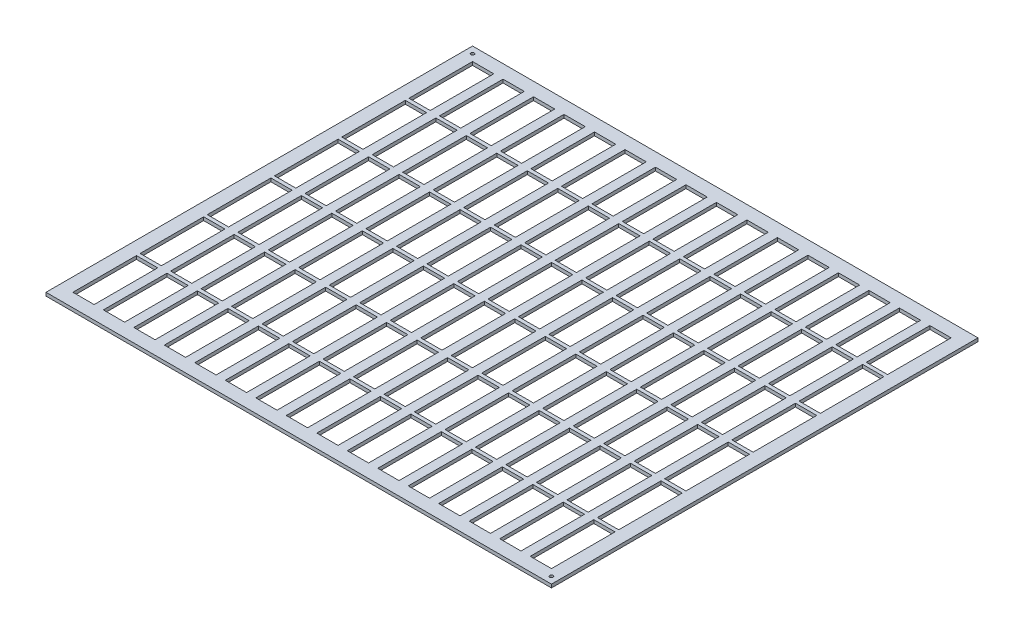
SolidWorks part; units mm, degrees
ref_plane "Front" through (0, 0, 0) normal (0, 0, 1) x (1, 0, 0)
ref_plane "Top" through (0, 0, 0) normal (0, 1, 0) x (1, 0, 0)
ref_plane "Right" through (0, 0, 0) normal (1, 0, 0) x (0, 0, -1)
sketch "Sketch1" plane through (0, 0, 0) normal (0, 1, 0) x (1, 0, 0)
  line L0 (0, -76.0537) -> (0, -227.7466) construction
  line L5 (-238.9187, -201.6125) -> (238.9188, -201.6125)
  line L6 (-238.9187, -201.6125) -> (-238.9187, 201.6125)
  line L7 (-238.9187, 201.6125) -> (238.9188, 201.6125)
  line L8 (238.9188, -201.6125) -> (238.9188, 201.6125)
  line L9 (-238.9187, -201.6125) -> (238.9188, 201.6125) construction
  line L10 (-238.9187, 201.6125) -> (238.9188, -201.6125) construction
  line L11 (55.3206, 0) -> (102.8784, 0) construction
  point P0 (0, 0)
  dimension "D1" = 477.8375
  dimension "D2" = 403.225
extrude "Boss-Extrude1" add sketch "Sketch1" along normal blind 3.175
sketch "Sketch2" plane through (0, 0, 0) normal (0, 1, 0) x (1, 0, 0)
  line L1 (-226.2187, 188.9125) -> (-206.1187, 188.9125)
  line L2 (-226.2187, 188.9125) -> (-226.2187, 128.8125)
  line L3 (-226.2187, 128.8125) -> (-206.1187, 128.8125)
  line L4 (-206.1187, 188.9125) -> (-206.1187, 128.8125)
  line L8 (206.1188, -128.8125) -> (226.2188, -128.8125) construction
  line L9 (206.1188, -128.8125) -> (206.1188, -188.9125) construction
  line L10 (206.1188, -188.9125) -> (226.2188, -188.9125) construction
  line L11 (226.2188, -128.8125) -> (226.2188, -188.9125) construction
  line L12 (-226.2187, -188.9125) -> (226.2188, -188.9125)
  line L13 (226.2188, -188.9125) -> (226.2188, 188.9125)
  line L14 (226.2188, 188.9125) -> (-226.2187, 188.9125)
  line L15 (-226.2187, 188.9125) -> (-226.2187, -188.9125)
  line L16 (-226.2187, -188.9125) -> (226.2188, -188.9125) construction
  line L17 (226.2188, -188.9125) -> (226.2188, 188.9125) construction
  line L18 (226.2188, 188.9125) -> (-226.2187, 188.9125) construction
  line L19 (-226.2187, 188.9125) -> (-226.2187, -188.9125) construction
  line L20 (216.1688, -128.8125) -> (216.1688, -188.9125) construction
  line L21 (206.1188, -158.8625) -> (226.2188, -158.8625) construction
  dimension "D1" = 60.1
  dimension "D2" = 20.1
  dimension "D3" = 12.7
extrude "Cut-Extrude1" cut sketch "Sketch2" along normal through all
pattern_linear "LPattern2" count 16 spacing 28.8225 along (1, 0, 0) count 6 spacing 63.545 along (0, 0, 1) of "Cut-Extrude1"
sketch "Sketch4" plane through (0, 0, 0) normal (0, 1, 0) x (1, 0, 0)
  line L0 (-238.9187, -201.6125) -> (238.9188, -201.6125) construction
  line L1 (238.9188, -201.6125) -> (238.9188, 201.6125) construction
  line L2 (238.9188, 201.6125) -> (-238.9187, 201.6125) construction
  line L3 (-238.9187, 201.6125) -> (-238.9187, -201.6125) construction
  circle A0 centre (-232.5687, 195.2625) radius 1.5875
  circle A1 centre (232.5688, -195.2625) radius 1.5875
  dimension "D3" = 3.175
  dimension "D6" = 3.175
  dimension "D1" = 6.35
  dimension "D2" = 6.35
  dimension "D4" = 6.35
  dimension "D5" = 6.35
extrude "Cut-Extrude2" cut sketch "Sketch4" along normal through all
sketch "v1" plane through (0, 0, 0) normal (0, 1, 0) x (1, 0, 0)
  line L0 (238.9188, -201.6125) -> (238.9188, 201.6125) construction
  line L9 (-238.9187, -201.6125) -> (238.9188, -201.6125) construction
  line L10 (-238.9187, 201.6125) -> (-238.9187, -201.6125) construction
  line L11 (238.9188, 201.6125) -> (-238.9187, 201.6125) construction
  line L12 (238.9188, -201.6125) -> (238.9188, 201.6125)
  line L13 (-238.9187, -201.6125) -> (238.9188, -201.6125)
  line L14 (-238.9187, 201.6125) -> (-238.9187, -201.6125)
  line L15 (238.9188, 201.6125) -> (-238.9187, 201.6125)
  line L16 (-206.1187, 128.8125) -> (-206.1187, 188.9125) construction
  line L17 (-206.1187, 188.9125) -> (-226.2187, 188.9125) construction
  line L18 (-226.2187, 128.8125) -> (-206.1187, 128.8125) construction
  line L19 (-226.2187, 188.9125) -> (-226.2187, 128.8125) construction
  line L20 (-226.2187, 128.8125) -> (-206.1187, 128.8125)
  line L21 (-206.1187, 188.9125) -> (-226.2187, 188.9125)
  line L22 (-206.1187, 128.8125) -> (-206.1187, 188.9125)
  line L23 (-226.2187, 188.9125) -> (-226.2187, 128.8125)
  line L24 (-180.7187, 188.9125) -> (-200.8187, 188.9125)
  line L25 (-226.2187, 188.9125) -> (-206.1187, 188.9125)
  line L26 (-226.2187, 188.9125) -> (-226.2187, 128.8125)
  line L27 (-226.2187, 128.8125) -> (-206.1187, 128.8125)
  line L28 (-206.1187, 188.9125) -> (-206.1187, 128.8125)
  line L29 (-200.8187, 188.9125) -> (-200.8187, 128.8125)
  line L30 (-200.8187, 128.8125) -> (-180.7187, 128.8125)
  line L31 (-180.7187, 128.8125) -> (-180.7187, 188.9125)
  line L32 (-155.3187, 188.9125) -> (-175.4187, 188.9125)
  line L33 (-175.4187, 188.9125) -> (-175.4187, 128.8125)
  line L34 (-175.4187, 128.8125) -> (-155.3187, 128.8125)
  line L35 (-155.3187, 128.8125) -> (-155.3187, 188.9125)
  line L36 (-129.9187, 188.9125) -> (-150.0187, 188.9125)
  line L37 (-150.0187, 188.9125) -> (-150.0187, 128.8125)
  line L38 (-150.0187, 128.8125) -> (-129.9187, 128.8125)
  line L39 (-129.9187, 128.8125) -> (-129.9187, 188.9125)
  line L40 (-104.5187, 188.9125) -> (-124.6187, 188.9125)
  line L41 (-124.6187, 188.9125) -> (-124.6187, 128.8125)
  line L42 (-124.6187, 128.8125) -> (-104.5187, 128.8125)
  line L43 (-104.5187, 128.8125) -> (-104.5187, 188.9125)
  line L44 (-79.1187, 188.9125) -> (-99.2187, 188.9125)
  line L45 (-99.2187, 188.9125) -> (-99.2187, 128.8125)
  line L46 (-99.2187, 128.8125) -> (-79.1187, 128.8125)
  line L47 (-79.1187, 128.8125) -> (-79.1187, 188.9125)
  line L48 (-53.7187, 188.9125) -> (-73.8187, 188.9125)
  line L49 (-73.8187, 188.9125) -> (-73.8187, 128.8125)
  line L50 (-73.8187, 128.8125) -> (-53.7187, 128.8125)
  line L51 (-53.7187, 128.8125) -> (-53.7187, 188.9125)
  line L52 (-28.3187, 188.9125) -> (-48.4187, 188.9125)
  line L53 (-48.4187, 188.9125) -> (-48.4187, 128.8125)
  line L54 (-48.4187, 128.8125) -> (-28.3187, 128.8125)
  line L55 (-28.3187, 128.8125) -> (-28.3187, 188.9125)
  line L56 (-2.9187, 188.9125) -> (-23.0187, 188.9125)
  line L57 (-23.0187, 188.9125) -> (-23.0187, 128.8125)
  line L58 (-23.0187, 128.8125) -> (-2.9187, 128.8125)
  line L59 (-2.9187, 128.8125) -> (-2.9187, 188.9125)
  line L60 (22.4813, 188.9125) -> (2.3813, 188.9125)
  line L61 (2.3813, 188.9125) -> (2.3813, 128.8125)
  line L62 (2.3813, 128.8125) -> (22.4813, 128.8125)
  line L63 (22.4813, 128.8125) -> (22.4813, 188.9125)
  line L64 (47.8813, 188.9125) -> (27.7813, 188.9125)
  line L65 (27.7813, 188.9125) -> (27.7813, 128.8125)
  line L66 (27.7813, 128.8125) -> (47.8813, 128.8125)
  line L67 (47.8813, 128.8125) -> (47.8813, 188.9125)
  line L68 (73.2813, 188.9125) -> (53.1813, 188.9125)
  line L69 (53.1813, 188.9125) -> (53.1813, 128.8125)
  line L70 (53.1813, 128.8125) -> (73.2813, 128.8125)
  line L71 (73.2813, 128.8125) -> (73.2813, 188.9125)
  line L72 (98.6813, 188.9125) -> (78.5813, 188.9125)
  line L73 (78.5813, 188.9125) -> (78.5813, 128.8125)
  line L74 (78.5813, 128.8125) -> (98.6813, 128.8125)
  line L75 (98.6813, 128.8125) -> (98.6813, 188.9125)
  line L76 (124.0813, 188.9125) -> (103.9813, 188.9125)
  line L77 (103.9813, 188.9125) -> (103.9813, 128.8125)
  line L78 (103.9813, 128.8125) -> (124.0813, 128.8125)
  line L79 (124.0813, 128.8125) -> (124.0813, 188.9125)
  line L80 (149.4813, 188.9125) -> (129.3813, 188.9125)
  line L81 (129.3813, 188.9125) -> (129.3813, 128.8125)
  line L82 (129.3813, 128.8125) -> (149.4813, 128.8125)
  line L83 (149.4813, 128.8125) -> (149.4813, 188.9125)
  line L84 (174.8813, 188.9125) -> (154.7813, 188.9125)
  line L85 (154.7813, 188.9125) -> (154.7813, 128.8125)
  line L86 (154.7813, 128.8125) -> (174.8813, 128.8125)
  line L87 (174.8813, 128.8125) -> (174.8813, 188.9125)
  line L88 (-180.7187, 125.4125) -> (-200.8187, 125.4125)
  line L89 (-200.8187, 125.4125) -> (-200.8187, 65.3125)
  line L90 (-200.8187, 65.3125) -> (-180.7187, 65.3125)
  line L91 (-180.7187, 65.3125) -> (-180.7187, 125.4125)
  line L92 (-155.3187, 125.4125) -> (-175.4187, 125.4125)
  line L93 (-175.4187, 125.4125) -> (-175.4187, 65.3125)
  line L94 (-175.4187, 65.3125) -> (-155.3187, 65.3125)
  line L95 (-155.3187, 65.3125) -> (-155.3187, 125.4125)
  line L96 (-129.9187, 125.4125) -> (-150.0187, 125.4125)
  line L97 (-150.0187, 125.4125) -> (-150.0187, 65.3125)
  line L98 (-150.0187, 65.3125) -> (-129.9187, 65.3125)
  line L99 (-129.9187, 65.3125) -> (-129.9187, 125.4125)
  line L100 (-104.5187, 125.4125) -> (-124.6187, 125.4125)
  line L101 (-124.6187, 125.4125) -> (-124.6187, 65.3125)
  line L102 (-124.6187, 65.3125) -> (-104.5187, 65.3125)
  line L103 (-104.5187, 65.3125) -> (-104.5187, 125.4125)
  line L104 (-79.1187, 125.4125) -> (-99.2187, 125.4125)
  line L105 (-99.2187, 125.4125) -> (-99.2187, 65.3125)
  line L106 (-99.2187, 65.3125) -> (-79.1187, 65.3125)
  line L107 (-79.1187, 65.3125) -> (-79.1187, 125.4125)
  line L108 (-53.7187, 125.4125) -> (-73.8187, 125.4125)
  line L109 (-73.8187, 125.4125) -> (-73.8187, 65.3125)
  line L110 (-73.8187, 65.3125) -> (-53.7187, 65.3125)
  line L111 (-53.7187, 65.3125) -> (-53.7187, 125.4125)
  line L112 (-28.3187, 125.4125) -> (-48.4187, 125.4125)
  line L113 (-48.4187, 125.4125) -> (-48.4187, 65.3125)
  line L114 (-48.4187, 65.3125) -> (-28.3187, 65.3125)
  line L115 (-28.3187, 65.3125) -> (-28.3187, 125.4125)
  line L116 (-2.9187, 125.4125) -> (-23.0187, 125.4125)
  line L117 (-23.0187, 125.4125) -> (-23.0187, 65.3125)
  line L118 (-23.0187, 65.3125) -> (-2.9187, 65.3125)
  line L119 (-2.9187, 65.3125) -> (-2.9187, 125.4125)
  line L120 (22.4813, 125.4125) -> (2.3813, 125.4125)
  line L121 (2.3813, 125.4125) -> (2.3813, 65.3125)
  line L122 (2.3813, 65.3125) -> (22.4813, 65.3125)
  line L123 (22.4813, 65.3125) -> (22.4813, 125.4125)
  line L124 (47.8813, 125.4125) -> (27.7813, 125.4125)
  line L125 (27.7813, 125.4125) -> (27.7813, 65.3125)
  line L126 (27.7813, 65.3125) -> (47.8813, 65.3125)
  line L127 (47.8813, 65.3125) -> (47.8813, 125.4125)
  line L128 (73.2813, 125.4125) -> (53.1813, 125.4125)
  line L129 (53.1813, 125.4125) -> (53.1813, 65.3125)
  line L130 (53.1813, 65.3125) -> (73.2813, 65.3125)
  line L131 (73.2813, 65.3125) -> (73.2813, 125.4125)
  line L132 (98.6813, 125.4125) -> (78.5813, 125.4125)
  line L133 (78.5813, 125.4125) -> (78.5813, 65.3125)
  line L134 (78.5813, 65.3125) -> (98.6813, 65.3125)
  line L135 (98.6813, 65.3125) -> (98.6813, 125.4125)
  line L136 (124.0813, 125.4125) -> (103.9813, 125.4125)
  line L137 (103.9813, 125.4125) -> (103.9813, 65.3125)
  line L138 (103.9813, 65.3125) -> (124.0813, 65.3125)
  line L139 (124.0813, 65.3125) -> (124.0813, 125.4125)
  line L140 (149.4813, 125.4125) -> (129.3813, 125.4125)
  line L141 (129.3813, 125.4125) -> (129.3813, 65.3125)
  line L142 (129.3813, 65.3125) -> (149.4813, 65.3125)
  line L143 (149.4813, 65.3125) -> (149.4813, 125.4125)
  line L144 (174.8813, 125.4125) -> (154.7813, 125.4125)
  line L145 (154.7813, 125.4125) -> (154.7813, 65.3125)
  line L146 (154.7813, 65.3125) -> (174.8813, 65.3125)
  line L147 (174.8813, 65.3125) -> (174.8813, 125.4125)
  line L148 (-180.7187, 61.9125) -> (-200.8187, 61.9125)
  line L149 (-200.8187, 61.9125) -> (-200.8187, 1.8125)
  line L150 (-200.8187, 1.8125) -> (-180.7187, 1.8125)
  line L151 (-180.7187, 1.8125) -> (-180.7187, 61.9125)
  line L152 (-155.3187, 61.9125) -> (-175.4187, 61.9125)
  line L153 (-175.4187, 61.9125) -> (-175.4187, 1.8125)
  line L154 (-175.4187, 1.8125) -> (-155.3187, 1.8125)
  line L155 (-155.3187, 1.8125) -> (-155.3187, 61.9125)
  line L156 (-129.9187, 61.9125) -> (-150.0187, 61.9125)
  line L157 (-150.0187, 61.9125) -> (-150.0187, 1.8125)
  line L158 (-150.0187, 1.8125) -> (-129.9187, 1.8125)
  line L159 (-129.9187, 1.8125) -> (-129.9187, 61.9125)
  line L160 (-104.5187, 61.9125) -> (-124.6187, 61.9125)
  line L161 (-124.6187, 61.9125) -> (-124.6187, 1.8125)
  line L162 (-124.6187, 1.8125) -> (-104.5187, 1.8125)
  line L163 (-104.5187, 1.8125) -> (-104.5187, 61.9125)
  line L164 (-79.1187, 61.9125) -> (-99.2187, 61.9125)
  line L165 (-99.2187, 61.9125) -> (-99.2187, 1.8125)
  line L166 (-99.2187, 1.8125) -> (-79.1187, 1.8125)
  line L167 (-79.1187, 1.8125) -> (-79.1187, 61.9125)
  line L168 (-53.7187, 61.9125) -> (-73.8187, 61.9125)
  line L169 (-73.8187, 61.9125) -> (-73.8187, 1.8125)
  line L170 (-73.8187, 1.8125) -> (-53.7187, 1.8125)
  line L171 (-53.7187, 1.8125) -> (-53.7187, 61.9125)
  line L172 (-28.3187, 61.9125) -> (-48.4187, 61.9125)
  line L173 (-48.4187, 61.9125) -> (-48.4187, 1.8125)
  line L174 (-48.4187, 1.8125) -> (-28.3187, 1.8125)
  line L175 (-28.3187, 1.8125) -> (-28.3187, 61.9125)
  line L176 (-2.9187, 61.9125) -> (-23.0187, 61.9125)
  line L177 (-23.0187, 61.9125) -> (-23.0187, 1.8125)
  line L178 (-23.0187, 1.8125) -> (-2.9187, 1.8125)
  line L179 (-2.9187, 1.8125) -> (-2.9187, 61.9125)
  line L180 (22.4813, 61.9125) -> (2.3813, 61.9125)
  line L181 (2.3813, 61.9125) -> (2.3813, 1.8125)
  line L182 (2.3813, 1.8125) -> (22.4813, 1.8125)
  line L183 (22.4813, 1.8125) -> (22.4813, 61.9125)
  line L184 (47.8813, 61.9125) -> (27.7813, 61.9125)
  line L185 (27.7813, 61.9125) -> (27.7813, 1.8125)
  line L186 (27.7813, 1.8125) -> (47.8813, 1.8125)
  line L187 (47.8813, 1.8125) -> (47.8813, 61.9125)
  line L188 (73.2813, 61.9125) -> (53.1813, 61.9125)
  line L189 (53.1813, 61.9125) -> (53.1813, 1.8125)
  line L190 (53.1813, 1.8125) -> (73.2813, 1.8125)
  line L191 (73.2813, 1.8125) -> (73.2813, 61.9125)
  line L192 (98.6813, 61.9125) -> (78.5813, 61.9125)
  line L193 (78.5813, 61.9125) -> (78.5813, 1.8125)
  line L194 (78.5813, 1.8125) -> (98.6813, 1.8125)
  line L195 (98.6813, 1.8125) -> (98.6813, 61.9125)
  line L196 (124.0813, 61.9125) -> (103.9813, 61.9125)
  line L197 (103.9813, 61.9125) -> (103.9813, 1.8125)
  line L198 (103.9813, 1.8125) -> (124.0813, 1.8125)
  line L199 (124.0813, 1.8125) -> (124.0813, 61.9125)
  line L200 (149.4813, 61.9125) -> (129.3813, 61.9125)
  line L201 (129.3813, 61.9125) -> (129.3813, 1.8125)
  line L202 (129.3813, 1.8125) -> (149.4813, 1.8125)
  line L203 (149.4813, 1.8125) -> (149.4813, 61.9125)
  line L204 (174.8813, 61.9125) -> (154.7813, 61.9125)
  line L205 (154.7813, 61.9125) -> (154.7813, 1.8125)
  line L206 (154.7813, 1.8125) -> (174.8813, 1.8125)
  line L207 (174.8813, 1.8125) -> (174.8813, 61.9125)
  line L208 (-180.7187, -1.5875) -> (-200.8187, -1.5875)
  line L209 (-200.8187, -1.5875) -> (-200.8187, -61.6875)
  line L210 (-200.8187, -61.6875) -> (-180.7187, -61.6875)
  line L211 (-180.7187, -61.6875) -> (-180.7187, -1.5875)
  line L212 (-155.3187, -1.5875) -> (-175.4187, -1.5875)
  line L213 (-175.4187, -1.5875) -> (-175.4187, -61.6875)
  line L214 (-175.4187, -61.6875) -> (-155.3187, -61.6875)
  line L215 (-155.3187, -61.6875) -> (-155.3187, -1.5875)
  line L216 (-129.9187, -1.5875) -> (-150.0187, -1.5875)
  line L217 (-150.0187, -1.5875) -> (-150.0187, -61.6875)
  line L218 (-150.0187, -61.6875) -> (-129.9187, -61.6875)
  line L219 (-129.9187, -61.6875) -> (-129.9187, -1.5875)
  line L220 (-104.5187, -1.5875) -> (-124.6187, -1.5875)
  line L221 (-124.6187, -1.5875) -> (-124.6187, -61.6875)
  line L222 (-124.6187, -61.6875) -> (-104.5187, -61.6875)
  line L223 (-104.5187, -61.6875) -> (-104.5187, -1.5875)
  line L224 (-79.1187, -1.5875) -> (-99.2187, -1.5875)
  line L225 (-99.2187, -1.5875) -> (-99.2187, -61.6875)
  line L226 (-99.2187, -61.6875) -> (-79.1187, -61.6875)
  line L227 (-79.1187, -61.6875) -> (-79.1187, -1.5875)
  line L228 (-53.7187, -1.5875) -> (-73.8187, -1.5875)
  line L229 (-73.8187, -1.5875) -> (-73.8187, -61.6875)
  line L230 (-73.8187, -61.6875) -> (-53.7187, -61.6875)
  line L231 (-53.7187, -61.6875) -> (-53.7187, -1.5875)
  line L232 (-28.3187, -1.5875) -> (-48.4187, -1.5875)
  line L233 (-48.4187, -1.5875) -> (-48.4187, -61.6875)
  line L234 (-48.4187, -61.6875) -> (-28.3187, -61.6875)
  line L235 (-28.3187, -61.6875) -> (-28.3187, -1.5875)
  line L236 (-2.9187, -1.5875) -> (-23.0187, -1.5875)
  line L237 (-23.0187, -1.5875) -> (-23.0187, -61.6875)
  line L238 (-23.0187, -61.6875) -> (-2.9187, -61.6875)
  line L239 (-2.9187, -61.6875) -> (-2.9187, -1.5875)
  line L240 (22.4813, -1.5875) -> (2.3813, -1.5875)
  line L241 (2.3813, -1.5875) -> (2.3813, -61.6875)
  line L242 (2.3813, -61.6875) -> (22.4813, -61.6875)
  line L243 (22.4813, -61.6875) -> (22.4813, -1.5875)
  line L244 (47.8813, -1.5875) -> (27.7813, -1.5875)
  line L245 (27.7813, -1.5875) -> (27.7813, -61.6875)
  line L246 (27.7813, -61.6875) -> (47.8813, -61.6875)
  line L247 (47.8813, -61.6875) -> (47.8813, -1.5875)
  line L248 (73.2813, -1.5875) -> (53.1813, -1.5875)
  line L249 (53.1813, -1.5875) -> (53.1813, -61.6875)
  line L250 (53.1813, -61.6875) -> (73.2813, -61.6875)
  line L251 (73.2813, -61.6875) -> (73.2813, -1.5875)
  line L252 (98.6813, -1.5875) -> (78.5813, -1.5875)
  line L253 (78.5813, -1.5875) -> (78.5813, -61.6875)
  line L254 (78.5813, -61.6875) -> (98.6813, -61.6875)
  line L255 (98.6813, -61.6875) -> (98.6813, -1.5875)
  line L256 (124.0813, -1.5875) -> (103.9813, -1.5875)
  line L257 (103.9813, -1.5875) -> (103.9813, -61.6875)
  line L258 (103.9813, -61.6875) -> (124.0813, -61.6875)
  line L259 (124.0813, -61.6875) -> (124.0813, -1.5875)
  line L260 (149.4813, -1.5875) -> (129.3813, -1.5875)
  line L261 (129.3813, -1.5875) -> (129.3813, -61.6875)
  line L262 (129.3813, -61.6875) -> (149.4813, -61.6875)
  line L263 (149.4813, -61.6875) -> (149.4813, -1.5875)
  line L264 (174.8813, -1.5875) -> (154.7813, -1.5875)
  line L265 (154.7813, -1.5875) -> (154.7813, -61.6875)
  line L266 (154.7813, -61.6875) -> (174.8813, -61.6875)
  line L267 (174.8813, -61.6875) -> (174.8813, -1.5875)
  line L268 (-180.7187, -65.0875) -> (-200.8187, -65.0875)
  line L269 (-200.8187, -65.0875) -> (-200.8187, -125.1875)
  line L270 (-200.8187, -125.1875) -> (-180.7187, -125.1875)
  line L271 (-180.7187, -125.1875) -> (-180.7187, -65.0875)
  line L272 (-155.3187, -65.0875) -> (-175.4187, -65.0875)
  line L273 (-175.4187, -65.0875) -> (-175.4187, -125.1875)
  line L274 (-175.4187, -125.1875) -> (-155.3187, -125.1875)
  line L275 (-155.3187, -125.1875) -> (-155.3187, -65.0875)
  line L276 (-129.9187, -65.0875) -> (-150.0187, -65.0875)
  line L277 (-150.0187, -65.0875) -> (-150.0187, -125.1875)
  line L278 (-150.0187, -125.1875) -> (-129.9187, -125.1875)
  line L279 (-129.9187, -125.1875) -> (-129.9187, -65.0875)
  line L280 (-104.5187, -65.0875) -> (-124.6187, -65.0875)
  line L281 (-124.6187, -65.0875) -> (-124.6187, -125.1875)
  line L282 (-124.6187, -125.1875) -> (-104.5187, -125.1875)
  line L283 (-104.5187, -125.1875) -> (-104.5187, -65.0875)
  line L284 (-79.1187, -65.0875) -> (-99.2187, -65.0875)
  line L285 (-99.2187, -65.0875) -> (-99.2187, -125.1875)
  line L286 (-99.2187, -125.1875) -> (-79.1187, -125.1875)
  line L287 (-79.1187, -125.1875) -> (-79.1187, -65.0875)
  line L288 (-53.7187, -65.0875) -> (-73.8187, -65.0875)
  line L289 (-73.8187, -65.0875) -> (-73.8187, -125.1875)
  line L290 (-73.8187, -125.1875) -> (-53.7187, -125.1875)
  line L291 (-53.7187, -125.1875) -> (-53.7187, -65.0875)
  line L292 (-28.3187, -65.0875) -> (-48.4187, -65.0875)
  line L293 (-48.4187, -65.0875) -> (-48.4187, -125.1875)
  line L294 (-48.4187, -125.1875) -> (-28.3187, -125.1875)
  line L295 (-28.3187, -125.1875) -> (-28.3187, -65.0875)
  line L296 (-2.9187, -65.0875) -> (-23.0187, -65.0875)
  line L297 (-23.0187, -65.0875) -> (-23.0187, -125.1875)
  line L298 (-23.0187, -125.1875) -> (-2.9187, -125.1875)
  line L299 (-2.9187, -125.1875) -> (-2.9187, -65.0875)
  line L300 (22.4813, -65.0875) -> (2.3813, -65.0875)
  line L301 (2.3813, -65.0875) -> (2.3813, -125.1875)
  line L302 (2.3813, -125.1875) -> (22.4813, -125.1875)
  line L303 (22.4813, -125.1875) -> (22.4813, -65.0875)
  line L304 (47.8813, -65.0875) -> (27.7813, -65.0875)
  line L305 (27.7813, -65.0875) -> (27.7813, -125.1875)
  line L306 (27.7813, -125.1875) -> (47.8813, -125.1875)
  line L307 (47.8813, -125.1875) -> (47.8813, -65.0875)
  line L308 (73.2813, -65.0875) -> (53.1813, -65.0875)
  line L309 (53.1813, -65.0875) -> (53.1813, -125.1875)
  line L310 (53.1813, -125.1875) -> (73.2813, -125.1875)
  line L311 (73.2813, -125.1875) -> (73.2813, -65.0875)
  line L312 (98.6813, -65.0875) -> (78.5813, -65.0875)
  line L313 (78.5813, -65.0875) -> (78.5813, -125.1875)
  line L314 (78.5813, -125.1875) -> (98.6813, -125.1875)
  line L315 (98.6813, -125.1875) -> (98.6813, -65.0875)
  line L316 (124.0813, -65.0875) -> (103.9813, -65.0875)
  line L317 (103.9813, -65.0875) -> (103.9813, -125.1875)
  line L318 (103.9813, -125.1875) -> (124.0813, -125.1875)
  line L319 (124.0813, -125.1875) -> (124.0813, -65.0875)
  line L320 (149.4813, -65.0875) -> (129.3813, -65.0875)
  line L321 (129.3813, -65.0875) -> (129.3813, -125.1875)
  line L322 (129.3813, -125.1875) -> (149.4813, -125.1875)
  line L323 (149.4813, -125.1875) -> (149.4813, -65.0875)
  line L324 (174.8813, -65.0875) -> (154.7813, -65.0875)
  line L325 (154.7813, -65.0875) -> (154.7813, -125.1875)
  line L326 (154.7813, -125.1875) -> (174.8813, -125.1875)
  line L327 (174.8813, -125.1875) -> (174.8813, -65.0875)
  line L328 (-180.7187, -128.5875) -> (-200.8187, -128.5875)
  line L329 (-200.8187, -128.5875) -> (-200.8187, -188.6875)
  line L330 (-200.8187, -188.6875) -> (-180.7187, -188.6875)
  line L331 (-180.7187, -188.6875) -> (-180.7187, -128.5875)
  line L332 (-155.3187, -128.5875) -> (-175.4187, -128.5875)
  line L333 (-175.4187, -128.5875) -> (-175.4187, -188.6875)
  line L334 (-175.4187, -188.6875) -> (-155.3187, -188.6875)
  line L335 (-155.3187, -188.6875) -> (-155.3187, -128.5875)
  line L336 (-129.9187, -128.5875) -> (-150.0187, -128.5875)
  line L337 (-150.0187, -128.5875) -> (-150.0187, -188.6875)
  line L338 (-150.0187, -188.6875) -> (-129.9187, -188.6875)
  line L339 (-129.9187, -188.6875) -> (-129.9187, -128.5875)
  line L340 (-104.5187, -128.5875) -> (-124.6187, -128.5875)
  line L341 (-124.6187, -128.5875) -> (-124.6187, -188.6875)
  line L342 (-124.6187, -188.6875) -> (-104.5187, -188.6875)
  line L343 (-104.5187, -188.6875) -> (-104.5187, -128.5875)
  line L344 (-79.1187, -128.5875) -> (-99.2187, -128.5875)
  line L345 (-99.2187, -128.5875) -> (-99.2187, -188.6875)
  line L346 (-99.2187, -188.6875) -> (-79.1187, -188.6875)
  line L347 (-79.1187, -188.6875) -> (-79.1187, -128.5875)
  line L348 (-53.7187, -128.5875) -> (-73.8187, -128.5875)
  line L349 (-73.8187, -128.5875) -> (-73.8187, -188.6875)
  line L350 (-73.8187, -188.6875) -> (-53.7187, -188.6875)
  line L351 (-53.7187, -188.6875) -> (-53.7187, -128.5875)
  line L352 (-28.3187, -128.5875) -> (-48.4187, -128.5875)
  line L353 (-48.4187, -128.5875) -> (-48.4187, -188.6875)
  line L354 (-48.4187, -188.6875) -> (-28.3187, -188.6875)
  line L355 (-28.3187, -188.6875) -> (-28.3187, -128.5875)
  line L356 (-2.9187, -128.5875) -> (-23.0187, -128.5875)
  line L357 (-23.0187, -128.5875) -> (-23.0187, -188.6875)
  line L358 (-23.0187, -188.6875) -> (-2.9187, -188.6875)
  line L359 (-2.9187, -188.6875) -> (-2.9187, -128.5875)
  line L360 (22.4813, -128.5875) -> (2.3813, -128.5875)
  line L361 (2.3813, -128.5875) -> (2.3813, -188.6875)
  line L362 (2.3813, -188.6875) -> (22.4813, -188.6875)
  line L363 (22.4813, -188.6875) -> (22.4813, -128.5875)
  line L364 (47.8813, -128.5875) -> (27.7813, -128.5875)
  line L365 (27.7813, -128.5875) -> (27.7813, -188.6875)
  line L366 (27.7813, -188.6875) -> (47.8813, -188.6875)
  line L367 (47.8813, -188.6875) -> (47.8813, -128.5875)
  line L368 (73.2813, -128.5875) -> (53.1813, -128.5875)
  line L369 (53.1813, -128.5875) -> (53.1813, -188.6875)
  line L370 (53.1813, -188.6875) -> (73.2813, -188.6875)
  line L371 (73.2813, -188.6875) -> (73.2813, -128.5875)
  line L372 (98.6813, -128.5875) -> (78.5813, -128.5875)
  line L373 (78.5813, -128.5875) -> (78.5813, -188.6875)
  line L374 (78.5813, -188.6875) -> (98.6813, -188.6875)
  line L375 (98.6813, -188.6875) -> (98.6813, -128.5875)
  line L376 (124.0813, -128.5875) -> (103.9813, -128.5875)
  line L377 (103.9813, -128.5875) -> (103.9813, -188.6875)
  line L378 (103.9813, -188.6875) -> (124.0813, -188.6875)
  line L379 (124.0813, -188.6875) -> (124.0813, -128.5875)
  line L380 (149.4813, -128.5875) -> (129.3813, -128.5875)
  line L381 (129.3813, -128.5875) -> (129.3813, -188.6875)
  line L382 (129.3813, -188.6875) -> (149.4813, -188.6875)
  line L383 (149.4813, -188.6875) -> (149.4813, -128.5875)
  line L384 (174.8813, -128.5875) -> (154.7813, -128.5875)
  line L385 (154.7813, -128.5875) -> (154.7813, -188.6875)
  line L386 (154.7813, -188.6875) -> (174.8813, -188.6875)
  line L387 (174.8813, -188.6875) -> (174.8813, -128.5875)
  line L388 (-206.1187, 125.4125) -> (-226.2187, 125.4125)
  line L389 (-226.2187, 125.4125) -> (-226.2187, 65.3125)
  line L390 (-226.2187, 65.3125) -> (-206.1187, 65.3125)
  line L391 (-206.1187, 65.3125) -> (-206.1187, 125.4125)
  line L392 (-206.1187, 61.9125) -> (-226.2187, 61.9125)
  line L393 (-226.2187, 61.9125) -> (-226.2187, 1.8125)
  line L394 (-226.2187, 1.8125) -> (-206.1187, 1.8125)
  line L395 (-206.1187, 1.8125) -> (-206.1187, 61.9125)
  line L396 (-206.1187, -1.5875) -> (-226.2187, -1.5875)
  line L397 (-226.2187, -1.5875) -> (-226.2187, -61.6875)
  line L398 (-226.2187, -61.6875) -> (-206.1187, -61.6875)
  line L399 (-206.1187, -61.6875) -> (-206.1187, -1.5875)
  line L400 (-206.1187, -65.0875) -> (-226.2187, -65.0875)
  line L401 (-226.2187, -65.0875) -> (-226.2187, -125.1875)
  line L402 (-226.2187, -125.1875) -> (-206.1187, -125.1875)
  line L403 (-206.1187, -125.1875) -> (-206.1187, -65.0875)
  line L404 (-206.1187, -128.5875) -> (-226.2187, -128.5875)
  line L405 (-226.2187, -128.5875) -> (-226.2187, -188.6875)
  line L406 (-226.2187, -188.6875) -> (-206.1187, -188.6875)
  line L407 (-206.1187, -188.6875) -> (-206.1187, -128.5875)
  line L408 (-206.1187, 188.9125) -> (-180.7187, 188.9125) construction
  line L409 (-206.1187, 188.9125) -> (-206.1187, 125.4125) construction
  circle A0 centre (-232.5687, 195.2625) radius 1.5875 construction
  circle A1 centre (232.5688, -195.2625) radius 1.5875 construction
  circle A2 centre (-232.5687, 195.2625) radius 1.5875
  circle A3 centre (232.5688, -195.2625) radius 1.5875
  dimension "D3" = 25.4
  dimension "D4" = 63.5
  dimension "D5" = 20.1
  dimension "D6" = 60.1
  dimension "D1" = 16
  dimension "D2" = 6
sketch "v2" plane through (0, 0, 0) normal (0, 1, 0) x (1, 0, 0)
  line L0 (-226.2187, 111.9375) -> (-206.1187, 111.9375)
  line L3 (-226.2187, 188.9125) -> (-206.1187, 188.9125)
  line L28 (238.9188, -201.6125) -> (238.9188, 201.6125)
  line L29 (238.9188, 201.6125) -> (-238.9187, 201.6125)
  line L30 (-238.9187, 201.6125) -> (-238.9187, -201.6125)
  line L31 (-238.9187, -201.6125) -> (238.9188, -201.6125)
  line L32 (238.9188, -201.6125) -> (238.9188, 201.6125)
  line L33 (238.9188, 201.6125) -> (-238.9187, 201.6125)
  line L34 (-238.9187, 201.6125) -> (-238.9187, -201.6125)
  line L35 (-238.9187, -201.6125) -> (238.9188, -201.6125)
  line L36 (-226.2187, 188.9125) -> (-226.2187, 119.2125)
  line L37 (-226.2187, 119.2125) -> (-206.1187, 119.2125)
  line L38 (-206.1187, 188.9125) -> (-206.1187, 119.2125)
  line L39 (-226.2187, 111.9375) -> (-226.2187, 42.2375)
  line L40 (-226.2187, 42.2375) -> (-206.1187, 42.2375)
  line L41 (-206.1187, 111.9375) -> (-206.1187, 42.2375)
  line L42 (-226.2187, 34.9625) -> (-206.1187, 34.9625)
  line L43 (-226.2187, 34.9625) -> (-226.2187, -34.7375)
  line L44 (-226.2187, -34.7375) -> (-206.1187, -34.7375)
  line L45 (-206.1187, 34.9625) -> (-206.1187, -34.7375)
  line L46 (-226.2187, -42.0125) -> (-206.1187, -42.0125)
  line L47 (-226.2187, -42.0125) -> (-226.2187, -111.7125)
  line L48 (-226.2187, -111.7125) -> (-206.1187, -111.7125)
  line L49 (-206.1187, -42.0125) -> (-206.1187, -111.7125)
  line L50 (-226.2187, -118.9875) -> (-206.1187, -118.9875)
  line L51 (-226.2187, -118.9875) -> (-226.2187, -188.6875)
  line L52 (-226.2187, -188.6875) -> (-206.1187, -188.6875)
  line L53 (-206.1187, -118.9875) -> (-206.1187, -188.6875)
  line L54 (-226.2187, 188.9125) -> (-226.2187, 111.9375) construction
  line L57 (-200.8187, 111.9375) -> (-180.7187, 111.9375)
  line L58 (-200.8187, 111.9375) -> (-200.8187, 42.2375)
  line L59 (-200.8187, 42.2375) -> (-180.7187, 42.2375)
  line L60 (-180.7187, 111.9375) -> (-180.7187, 42.2375)
  line L61 (-200.8187, 34.9625) -> (-180.7187, 34.9625)
  line L62 (-200.8187, 34.9625) -> (-200.8187, -34.7375)
  line L63 (-200.8187, -34.7375) -> (-180.7187, -34.7375)
  line L64 (-180.7187, 34.9625) -> (-180.7187, -34.7375)
  line L65 (-200.8187, -42.0125) -> (-180.7187, -42.0125)
  line L66 (-200.8187, -42.0125) -> (-200.8187, -111.7125)
  line L67 (-200.8187, -111.7125) -> (-180.7187, -111.7125)
  line L68 (-180.7187, -42.0125) -> (-180.7187, -111.7125)
  line L69 (-200.8187, -118.9875) -> (-180.7187, -118.9875)
  line L70 (-200.8187, -118.9875) -> (-200.8187, -188.6875)
  line L71 (-200.8187, -188.6875) -> (-180.7187, -188.6875)
  line L72 (-180.7187, -118.9875) -> (-180.7187, -188.6875)
  line L73 (-200.8187, 188.9125) -> (-200.8187, 119.2125)
  line L74 (-200.8187, 188.9125) -> (-180.7187, 188.9125)
  line L75 (-180.7187, 188.9125) -> (-180.7187, 119.2125)
  line L76 (-200.8187, 119.2125) -> (-180.7187, 119.2125)
  line L77 (-175.4187, 111.9375) -> (-155.3187, 111.9375)
  line L78 (-175.4187, 111.9375) -> (-175.4187, 42.2375)
  line L79 (-175.4187, 42.2375) -> (-155.3187, 42.2375)
  line L80 (-155.3187, 111.9375) -> (-155.3187, 42.2375)
  line L81 (-175.4187, 34.9625) -> (-155.3187, 34.9625)
  line L82 (-175.4187, 34.9625) -> (-175.4187, -34.7375)
  line L83 (-175.4187, -34.7375) -> (-155.3187, -34.7375)
  line L84 (-155.3187, 34.9625) -> (-155.3187, -34.7375)
  line L85 (-175.4187, -42.0125) -> (-155.3187, -42.0125)
  line L86 (-175.4187, -42.0125) -> (-175.4187, -111.7125)
  line L87 (-175.4187, -111.7125) -> (-155.3187, -111.7125)
  line L88 (-155.3187, -42.0125) -> (-155.3187, -111.7125)
  line L89 (-175.4187, -118.9875) -> (-155.3187, -118.9875)
  line L90 (-175.4187, -118.9875) -> (-175.4187, -188.6875)
  line L91 (-175.4187, -188.6875) -> (-155.3187, -188.6875)
  line L92 (-155.3187, -118.9875) -> (-155.3187, -188.6875)
  line L93 (-175.4187, 188.9125) -> (-175.4187, 119.2125)
  line L94 (-175.4187, 188.9125) -> (-155.3187, 188.9125)
  line L95 (-155.3187, 188.9125) -> (-155.3187, 119.2125)
  line L96 (-175.4187, 119.2125) -> (-155.3187, 119.2125)
  line L97 (-150.0187, 111.9375) -> (-129.9187, 111.9375)
  line L98 (-150.0187, 111.9375) -> (-150.0187, 42.2375)
  line L99 (-150.0187, 42.2375) -> (-129.9187, 42.2375)
  line L100 (-129.9187, 111.9375) -> (-129.9187, 42.2375)
  line L101 (-150.0187, 34.9625) -> (-129.9187, 34.9625)
  line L102 (-150.0187, 34.9625) -> (-150.0187, -34.7375)
  line L103 (-150.0187, -34.7375) -> (-129.9187, -34.7375)
  line L104 (-129.9187, 34.9625) -> (-129.9187, -34.7375)
  line L105 (-150.0187, -42.0125) -> (-129.9187, -42.0125)
  line L106 (-150.0187, -42.0125) -> (-150.0187, -111.7125)
  line L107 (-150.0187, -111.7125) -> (-129.9187, -111.7125)
  line L108 (-129.9187, -42.0125) -> (-129.9187, -111.7125)
  line L109 (-150.0187, -118.9875) -> (-129.9187, -118.9875)
  line L110 (-150.0187, -118.9875) -> (-150.0187, -188.6875)
  line L111 (-150.0187, -188.6875) -> (-129.9187, -188.6875)
  line L112 (-129.9187, -118.9875) -> (-129.9187, -188.6875)
  line L113 (-150.0187, 188.9125) -> (-150.0187, 119.2125)
  line L114 (-150.0187, 188.9125) -> (-129.9187, 188.9125)
  line L115 (-129.9187, 188.9125) -> (-129.9187, 119.2125)
  line L116 (-150.0187, 119.2125) -> (-129.9187, 119.2125)
  line L117 (-124.6187, 111.9375) -> (-104.5187, 111.9375)
  line L118 (-124.6187, 111.9375) -> (-124.6187, 42.2375)
  line L119 (-124.6187, 42.2375) -> (-104.5187, 42.2375)
  line L120 (-104.5187, 111.9375) -> (-104.5187, 42.2375)
  line L121 (-124.6187, 34.9625) -> (-104.5187, 34.9625)
  line L122 (-124.6187, 34.9625) -> (-124.6187, -34.7375)
  line L123 (-124.6187, -34.7375) -> (-104.5187, -34.7375)
  line L124 (-104.5187, 34.9625) -> (-104.5187, -34.7375)
  line L125 (-124.6187, -42.0125) -> (-104.5187, -42.0125)
  line L126 (-124.6187, -42.0125) -> (-124.6187, -111.7125)
  line L127 (-124.6187, -111.7125) -> (-104.5187, -111.7125)
  line L128 (-104.5187, -42.0125) -> (-104.5187, -111.7125)
  line L129 (-124.6187, -118.9875) -> (-104.5187, -118.9875)
  line L130 (-124.6187, -118.9875) -> (-124.6187, -188.6875)
  line L131 (-124.6187, -188.6875) -> (-104.5187, -188.6875)
  line L132 (-104.5187, -118.9875) -> (-104.5187, -188.6875)
  line L133 (-124.6187, 188.9125) -> (-124.6187, 119.2125)
  line L134 (-124.6187, 188.9125) -> (-104.5187, 188.9125)
  line L135 (-104.5187, 188.9125) -> (-104.5187, 119.2125)
  line L136 (-124.6187, 119.2125) -> (-104.5187, 119.2125)
  line L137 (-99.2187, 111.9375) -> (-79.1187, 111.9375)
  line L138 (-99.2187, 111.9375) -> (-99.2187, 42.2375)
  line L139 (-99.2187, 42.2375) -> (-79.1187, 42.2375)
  line L140 (-79.1187, 111.9375) -> (-79.1187, 42.2375)
  line L141 (-99.2187, 34.9625) -> (-79.1187, 34.9625)
  line L142 (-99.2187, 34.9625) -> (-99.2187, -34.7375)
  line L143 (-99.2187, -34.7375) -> (-79.1187, -34.7375)
  line L144 (-79.1187, 34.9625) -> (-79.1187, -34.7375)
  line L145 (-99.2187, -42.0125) -> (-79.1187, -42.0125)
  line L146 (-99.2187, -42.0125) -> (-99.2187, -111.7125)
  line L147 (-99.2187, -111.7125) -> (-79.1187, -111.7125)
  line L148 (-79.1187, -42.0125) -> (-79.1187, -111.7125)
  line L149 (-99.2187, -118.9875) -> (-79.1187, -118.9875)
  line L150 (-99.2187, -118.9875) -> (-99.2187, -188.6875)
  line L151 (-99.2187, -188.6875) -> (-79.1187, -188.6875)
  line L152 (-79.1187, -118.9875) -> (-79.1187, -188.6875)
  line L153 (-99.2187, 188.9125) -> (-99.2187, 119.2125)
  line L154 (-99.2187, 188.9125) -> (-79.1187, 188.9125)
  line L155 (-79.1187, 188.9125) -> (-79.1187, 119.2125)
  line L156 (-99.2187, 119.2125) -> (-79.1187, 119.2125)
  line L157 (-73.8187, 111.9375) -> (-53.7187, 111.9375)
  line L158 (-73.8187, 111.9375) -> (-73.8187, 42.2375)
  line L159 (-73.8187, 42.2375) -> (-53.7187, 42.2375)
  line L160 (-53.7187, 111.9375) -> (-53.7187, 42.2375)
  line L161 (-73.8187, 34.9625) -> (-53.7187, 34.9625)
  line L162 (-73.8187, 34.9625) -> (-73.8187, -34.7375)
  line L163 (-73.8187, -34.7375) -> (-53.7187, -34.7375)
  line L164 (-53.7187, 34.9625) -> (-53.7187, -34.7375)
  line L165 (-73.8187, -42.0125) -> (-53.7187, -42.0125)
  line L166 (-73.8187, -42.0125) -> (-73.8187, -111.7125)
  line L167 (-73.8187, -111.7125) -> (-53.7187, -111.7125)
  line L168 (-53.7187, -42.0125) -> (-53.7187, -111.7125)
  line L169 (-73.8187, -118.9875) -> (-53.7187, -118.9875)
  line L170 (-73.8187, -118.9875) -> (-73.8187, -188.6875)
  line L171 (-73.8187, -188.6875) -> (-53.7187, -188.6875)
  line L172 (-53.7187, -118.9875) -> (-53.7187, -188.6875)
  line L173 (-73.8187, 188.9125) -> (-73.8187, 119.2125)
  line L174 (-73.8187, 188.9125) -> (-53.7187, 188.9125)
  line L175 (-53.7187, 188.9125) -> (-53.7187, 119.2125)
  line L176 (-73.8187, 119.2125) -> (-53.7187, 119.2125)
  line L177 (-48.4187, 111.9375) -> (-28.3187, 111.9375)
  line L178 (-48.4187, 111.9375) -> (-48.4187, 42.2375)
  line L179 (-48.4187, 42.2375) -> (-28.3187, 42.2375)
  line L180 (-28.3187, 111.9375) -> (-28.3187, 42.2375)
  line L181 (-48.4187, 34.9625) -> (-28.3187, 34.9625)
  line L182 (-48.4187, 34.9625) -> (-48.4187, -34.7375)
  line L183 (-48.4187, -34.7375) -> (-28.3187, -34.7375)
  line L184 (-28.3187, 34.9625) -> (-28.3187, -34.7375)
  line L185 (-48.4187, -42.0125) -> (-28.3187, -42.0125)
  line L186 (-48.4187, -42.0125) -> (-48.4187, -111.7125)
  line L187 (-48.4187, -111.7125) -> (-28.3187, -111.7125)
  line L188 (-28.3187, -42.0125) -> (-28.3187, -111.7125)
  line L189 (-48.4187, -118.9875) -> (-28.3187, -118.9875)
  line L190 (-48.4187, -118.9875) -> (-48.4187, -188.6875)
  line L191 (-48.4187, -188.6875) -> (-28.3187, -188.6875)
  line L192 (-28.3187, -118.9875) -> (-28.3187, -188.6875)
  line L193 (-48.4187, 188.9125) -> (-48.4187, 119.2125)
  line L194 (-48.4187, 188.9125) -> (-28.3187, 188.9125)
  line L195 (-28.3187, 188.9125) -> (-28.3187, 119.2125)
  line L196 (-48.4187, 119.2125) -> (-28.3187, 119.2125)
  line L197 (-23.0187, 111.9375) -> (-2.9187, 111.9375)
  line L198 (-23.0187, 111.9375) -> (-23.0187, 42.2375)
  line L199 (-23.0187, 42.2375) -> (-2.9187, 42.2375)
  line L200 (-2.9187, 111.9375) -> (-2.9187, 42.2375)
  line L201 (-23.0187, 34.9625) -> (-2.9187, 34.9625)
  line L202 (-23.0187, 34.9625) -> (-23.0187, -34.7375)
  line L203 (-23.0187, -34.7375) -> (-2.9187, -34.7375)
  line L204 (-2.9187, 34.9625) -> (-2.9187, -34.7375)
  line L205 (-23.0187, -42.0125) -> (-2.9187, -42.0125)
  line L206 (-23.0187, -42.0125) -> (-23.0187, -111.7125)
  line L207 (-23.0187, -111.7125) -> (-2.9187, -111.7125)
  line L208 (-2.9187, -42.0125) -> (-2.9187, -111.7125)
  line L209 (-23.0187, -118.9875) -> (-2.9187, -118.9875)
  line L210 (-23.0187, -118.9875) -> (-23.0187, -188.6875)
  line L211 (-23.0187, -188.6875) -> (-2.9187, -188.6875)
  line L212 (-2.9187, -118.9875) -> (-2.9187, -188.6875)
  line L213 (-23.0187, 188.9125) -> (-23.0187, 119.2125)
  line L214 (-23.0187, 188.9125) -> (-2.9187, 188.9125)
  line L215 (-2.9187, 188.9125) -> (-2.9187, 119.2125)
  line L216 (-23.0187, 119.2125) -> (-2.9187, 119.2125)
  line L217 (2.3813, 111.9375) -> (22.4813, 111.9375)
  line L218 (2.3813, 111.9375) -> (2.3813, 42.2375)
  line L219 (2.3813, 42.2375) -> (22.4813, 42.2375)
  line L220 (22.4813, 111.9375) -> (22.4813, 42.2375)
  line L221 (2.3813, 34.9625) -> (22.4813, 34.9625)
  line L222 (2.3813, 34.9625) -> (2.3813, -34.7375)
  line L223 (2.3813, -34.7375) -> (22.4813, -34.7375)
  line L224 (22.4813, 34.9625) -> (22.4813, -34.7375)
  line L225 (2.3813, -42.0125) -> (22.4813, -42.0125)
  line L226 (2.3813, -42.0125) -> (2.3813, -111.7125)
  line L227 (2.3813, -111.7125) -> (22.4813, -111.7125)
  line L228 (22.4813, -42.0125) -> (22.4813, -111.7125)
  line L229 (2.3813, -118.9875) -> (22.4813, -118.9875)
  line L230 (2.3813, -118.9875) -> (2.3813, -188.6875)
  line L231 (2.3813, -188.6875) -> (22.4813, -188.6875)
  line L232 (22.4813, -118.9875) -> (22.4813, -188.6875)
  line L233 (2.3813, 188.9125) -> (2.3813, 119.2125)
  line L234 (2.3813, 188.9125) -> (22.4813, 188.9125)
  line L235 (22.4813, 188.9125) -> (22.4813, 119.2125)
  line L236 (2.3813, 119.2125) -> (22.4813, 119.2125)
  line L237 (27.7813, 111.9375) -> (47.8813, 111.9375)
  line L238 (27.7813, 111.9375) -> (27.7813, 42.2375)
  line L239 (27.7813, 42.2375) -> (47.8813, 42.2375)
  line L240 (47.8813, 111.9375) -> (47.8813, 42.2375)
  line L241 (27.7813, 34.9625) -> (47.8813, 34.9625)
  line L242 (27.7813, 34.9625) -> (27.7813, -34.7375)
  line L243 (27.7813, -34.7375) -> (47.8813, -34.7375)
  line L244 (47.8813, 34.9625) -> (47.8813, -34.7375)
  line L245 (27.7813, -42.0125) -> (47.8813, -42.0125)
  line L246 (27.7813, -42.0125) -> (27.7813, -111.7125)
  line L247 (27.7813, -111.7125) -> (47.8813, -111.7125)
  line L248 (47.8813, -42.0125) -> (47.8813, -111.7125)
  line L249 (27.7813, -118.9875) -> (47.8813, -118.9875)
  line L250 (27.7813, -118.9875) -> (27.7813, -188.6875)
  line L251 (27.7813, -188.6875) -> (47.8813, -188.6875)
  line L252 (47.8813, -118.9875) -> (47.8813, -188.6875)
  line L253 (27.7813, 188.9125) -> (27.7813, 119.2125)
  line L254 (27.7813, 188.9125) -> (47.8813, 188.9125)
  line L255 (47.8813, 188.9125) -> (47.8813, 119.2125)
  line L256 (27.7813, 119.2125) -> (47.8813, 119.2125)
  line L257 (53.1813, 111.9375) -> (73.2813, 111.9375)
  line L258 (53.1813, 111.9375) -> (53.1813, 42.2375)
  line L259 (53.1813, 42.2375) -> (73.2813, 42.2375)
  line L260 (73.2813, 111.9375) -> (73.2813, 42.2375)
  line L261 (53.1813, 34.9625) -> (73.2813, 34.9625)
  line L262 (53.1813, 34.9625) -> (53.1813, -34.7375)
  line L263 (53.1813, -34.7375) -> (73.2813, -34.7375)
  line L264 (73.2813, 34.9625) -> (73.2813, -34.7375)
  line L265 (53.1813, -42.0125) -> (73.2813, -42.0125)
  line L266 (53.1813, -42.0125) -> (53.1813, -111.7125)
  line L267 (53.1813, -111.7125) -> (73.2813, -111.7125)
  line L268 (73.2813, -42.0125) -> (73.2813, -111.7125)
  line L269 (53.1813, -118.9875) -> (73.2813, -118.9875)
  line L270 (53.1813, -118.9875) -> (53.1813, -188.6875)
  line L271 (53.1813, -188.6875) -> (73.2813, -188.6875)
  line L272 (73.2813, -118.9875) -> (73.2813, -188.6875)
  line L273 (53.1813, 188.9125) -> (53.1813, 119.2125)
  line L274 (53.1813, 188.9125) -> (73.2813, 188.9125)
  line L275 (73.2813, 188.9125) -> (73.2813, 119.2125)
  line L276 (53.1813, 119.2125) -> (73.2813, 119.2125)
  line L277 (78.5813, 111.9375) -> (98.6813, 111.9375)
  line L278 (78.5813, 111.9375) -> (78.5813, 42.2375)
  line L279 (78.5813, 42.2375) -> (98.6813, 42.2375)
  line L280 (98.6813, 111.9375) -> (98.6813, 42.2375)
  line L281 (78.5813, 34.9625) -> (98.6813, 34.9625)
  line L282 (78.5813, 34.9625) -> (78.5813, -34.7375)
  line L283 (78.5813, -34.7375) -> (98.6813, -34.7375)
  line L284 (98.6813, 34.9625) -> (98.6813, -34.7375)
  line L285 (78.5813, -42.0125) -> (98.6813, -42.0125)
  line L286 (78.5813, -42.0125) -> (78.5813, -111.7125)
  line L287 (78.5813, -111.7125) -> (98.6813, -111.7125)
  line L288 (98.6813, -42.0125) -> (98.6813, -111.7125)
  line L289 (78.5813, -118.9875) -> (98.6813, -118.9875)
  line L290 (78.5813, -118.9875) -> (78.5813, -188.6875)
  line L291 (78.5813, -188.6875) -> (98.6813, -188.6875)
  line L292 (98.6813, -118.9875) -> (98.6813, -188.6875)
  line L293 (78.5813, 188.9125) -> (78.5813, 119.2125)
  line L294 (78.5813, 188.9125) -> (98.6813, 188.9125)
  line L295 (98.6813, 188.9125) -> (98.6813, 119.2125)
  line L296 (78.5813, 119.2125) -> (98.6813, 119.2125)
  line L297 (103.9813, 111.9375) -> (124.0813, 111.9375)
  line L298 (103.9813, 111.9375) -> (103.9813, 42.2375)
  line L299 (103.9813, 42.2375) -> (124.0813, 42.2375)
  line L300 (124.0813, 111.9375) -> (124.0813, 42.2375)
  line L301 (103.9813, 34.9625) -> (124.0813, 34.9625)
  line L302 (103.9813, 34.9625) -> (103.9813, -34.7375)
  line L303 (103.9813, -34.7375) -> (124.0813, -34.7375)
  line L304 (124.0813, 34.9625) -> (124.0813, -34.7375)
  line L305 (103.9813, -42.0125) -> (124.0813, -42.0125)
  line L306 (103.9813, -42.0125) -> (103.9813, -111.7125)
  line L307 (103.9813, -111.7125) -> (124.0813, -111.7125)
  line L308 (124.0813, -42.0125) -> (124.0813, -111.7125)
  line L309 (103.9813, -118.9875) -> (124.0813, -118.9875)
  line L310 (103.9813, -118.9875) -> (103.9813, -188.6875)
  line L311 (103.9813, -188.6875) -> (124.0813, -188.6875)
  line L312 (124.0813, -118.9875) -> (124.0813, -188.6875)
  line L313 (103.9813, 188.9125) -> (103.9813, 119.2125)
  line L314 (103.9813, 188.9125) -> (124.0813, 188.9125)
  line L315 (124.0813, 188.9125) -> (124.0813, 119.2125)
  line L316 (103.9813, 119.2125) -> (124.0813, 119.2125)
  line L317 (129.3813, 111.9375) -> (149.4813, 111.9375)
  line L318 (129.3813, 111.9375) -> (129.3813, 42.2375)
  line L319 (129.3813, 42.2375) -> (149.4813, 42.2375)
  line L320 (149.4813, 111.9375) -> (149.4813, 42.2375)
  line L321 (129.3813, 34.9625) -> (149.4813, 34.9625)
  line L322 (129.3813, 34.9625) -> (129.3813, -34.7375)
  line L323 (129.3813, -34.7375) -> (149.4813, -34.7375)
  line L324 (149.4813, 34.9625) -> (149.4813, -34.7375)
  line L325 (129.3813, -42.0125) -> (149.4813, -42.0125)
  line L326 (129.3813, -42.0125) -> (129.3813, -111.7125)
  line L327 (129.3813, -111.7125) -> (149.4813, -111.7125)
  line L328 (149.4813, -42.0125) -> (149.4813, -111.7125)
  line L329 (129.3813, -118.9875) -> (149.4813, -118.9875)
  line L330 (129.3813, -118.9875) -> (129.3813, -188.6875)
  line L331 (129.3813, -188.6875) -> (149.4813, -188.6875)
  line L332 (149.4813, -118.9875) -> (149.4813, -188.6875)
  line L333 (129.3813, 188.9125) -> (129.3813, 119.2125)
  line L334 (129.3813, 188.9125) -> (149.4813, 188.9125)
  line L335 (149.4813, 188.9125) -> (149.4813, 119.2125)
  line L336 (129.3813, 119.2125) -> (149.4813, 119.2125)
  line L337 (154.7813, 111.9375) -> (174.8813, 111.9375)
  line L338 (154.7813, 111.9375) -> (154.7813, 42.2375)
  line L339 (154.7813, 42.2375) -> (174.8813, 42.2375)
  line L340 (174.8813, 111.9375) -> (174.8813, 42.2375)
  line L341 (154.7813, 34.9625) -> (174.8813, 34.9625)
  line L342 (154.7813, 34.9625) -> (154.7813, -34.7375)
  line L343 (154.7813, -34.7375) -> (174.8813, -34.7375)
  line L344 (174.8813, 34.9625) -> (174.8813, -34.7375)
  line L345 (154.7813, -42.0125) -> (174.8813, -42.0125)
  line L346 (154.7813, -42.0125) -> (154.7813, -111.7125)
  line L347 (154.7813, -111.7125) -> (174.8813, -111.7125)
  line L348 (174.8813, -42.0125) -> (174.8813, -111.7125)
  line L349 (154.7813, -118.9875) -> (174.8813, -118.9875)
  line L350 (154.7813, -118.9875) -> (154.7813, -188.6875)
  line L351 (154.7813, -188.6875) -> (174.8813, -188.6875)
  line L352 (174.8813, -118.9875) -> (174.8813, -188.6875)
  line L353 (154.7813, 188.9125) -> (154.7813, 119.2125)
  line L354 (154.7813, 188.9125) -> (174.8813, 188.9125)
  line L355 (174.8813, 188.9125) -> (174.8813, 119.2125)
  line L356 (154.7813, 119.2125) -> (174.8813, 119.2125)
  line L397 (-226.2187, 111.9375) -> (-200.8187, 111.9375) construction
  circle A1 centre (232.5688, -195.2625) radius 1.5875
  circle A2 centre (232.5688, -195.2625) radius 1.5875
  circle A3 centre (-232.5687, 195.2625) radius 1.5875
  circle A4 centre (-232.5687, 195.2625) radius 1.5875
  point P0 (-226.2187, 188.9125)
  dimension "D3" = 69.7
  dimension "D4" = 20.1
  dimension "D7" = 76.975
  dimension "D9" = 25.4
  dimension "D1" = 0
  dimension "D2" = 0
  dimension "D5" = 5
  dimension "D6" = 0
  dimension "D8" = 16
